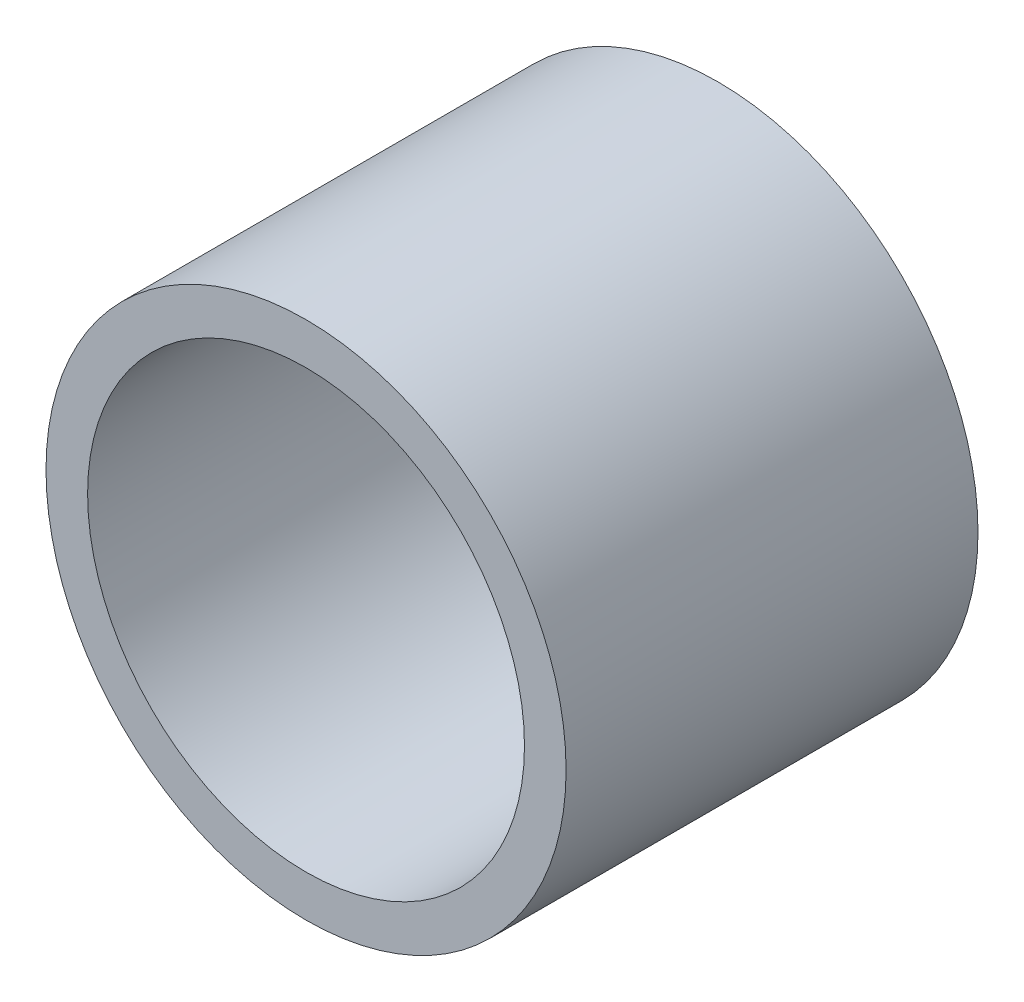
SolidWorks part; units mm, degrees
material "Bronze comercial com chumbo"
ref_plane "Plano frontal" through (0, 0, 0) normal (0, 0, 1) x (1, 0, 0)
ref_plane "Plano superior" through (0, 0, 0) normal (0, 1, 0) x (1, 0, 0)
ref_plane "Plano direito" through (0, 0, 0) normal (1, 0, 0) x (0, 0, -1)
sketch "Esboço1" plane through (0, 0, 0) normal (0, 0, 1) x (1, 0, 0)
  circle A0 centre (0, 0) radius 12.5
  circle A1 centre (0, 0) radius 10.5
  dimension "D1" = 25
  dimension "D2" = 21
extrude "Ressalto-extrusão1" add sketch "Esboço1" along normal blind 19.8
